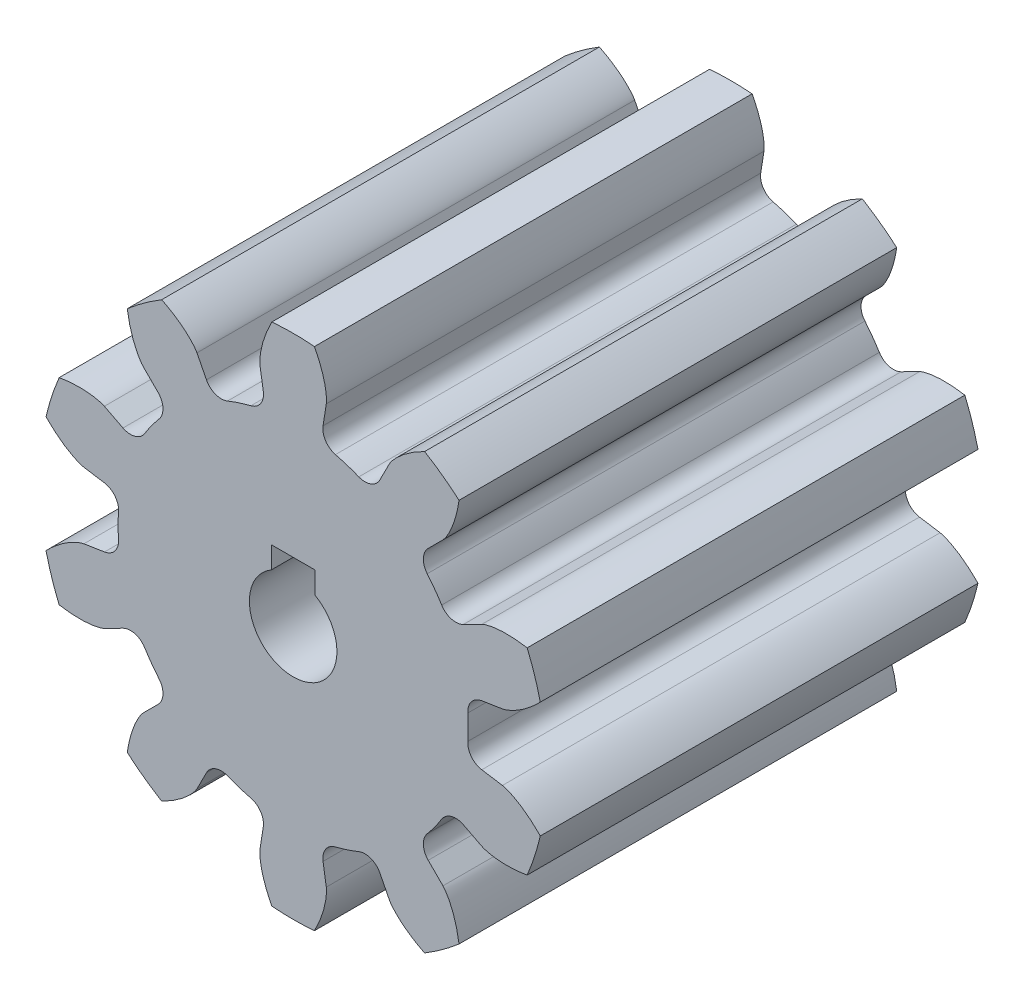
SolidWorks part; units mm, degrees
material "Plain Carbon Steel"
ref_plane "Front Plane" through (0, 0, 0) normal (0, 0, 1) x (1, 0, 0)
ref_plane "Top Plane" through (0, 0, 0) normal (0, 1, 0) x (1, 0, 0)
ref_plane "Right Plane" through (0, 0, 0) normal (1, 0, 0) x (0, 0, -1)
other "Configuration Table"
sketch "Base Circle Sketch" plane through (0, 0, 0) normal (0, 0, 1) x (1, 0, 0)
  circle A0 centre (0, 0) radius 9.6815 construction
  dimension "Base Circle" = 19.363
sketch "Pitch Circle Sketch" plane through (0, 0, 0) normal (0, 0, 1) x (1, 0, 0)
  circle A0 centre (0, 0) radius 10 construction
  dimension "Pitch Circle" = 20
sketch "Outer Dia Sketch" plane through (0, 0, 0) normal (0, 0, 1) x (1, 0, 0)
  circle A0 centre (0, 0) radius 11.6 construction
  dimension "Outer Diameter" = 23.2
sketch "Root Dia Sketch" plane through (0, 0, 0) normal (0, 0, 1) x (1, 0, 0)
  circle A0 centre (0, 0) radius 8
  dimension "Root Circle" = 16
sketch "Involute Sketch" plane through (0, 0, 0) normal (0, 0, 1) x (1, 0, 0)
  line L0 (0, 0) -> (1.5145, 9.5623) construction
  line L2 (0, 0) -> (-1.5145, 9.5623) construction
  line L4 (0, 0) -> (0, 9.6815) construction
  circle A0 centre (0, 0) radius 9.6815 construction
  spline S0 degree 4 poles (1.5145, 9.5623) (1.5152, 9.5666) (1.5169, 9.5789) (1.5193, 9.6022) (1.5218, 9.6404) (1.5232, 9.6893) (1.5229, 9.7525) (1.5198, 9.8272) (1.5134, 9.9092) (1.5034, 9.9985) (1.4907, 10.0875) (1.4754, 10.1761) (1.4579, 10.2642) (1.434, 10.3707) (1.4015, 10.498) (1.3581, 10.6462) (1.3025, 10.8132) (1.239, 10.9822) (1.171, 11.1474) (1.0959, 11.3129) (1.0188, 11.4719) (0.9324, 11.6353) (0.8493, 11.7852) (0.7493, 11.9511) (0.6665, 12.0843) (0.5501, 12.2574) (0.4791, 12.3589) (0.3937, 12.4767) (0.3544, 12.5286) (0.3302, 12.5605) knots 0 0 0 0 0 0.005377 0.015084 0.028532 0.04661 0.064855 0.092111 0.119476 0.146842 0.174209 0.201575 0.228941 0.256307 0.307035 0.361767 0.4165 0.471232 0.525964 0.580697 0.635429 0.690161 0.744894 0.799626 0.854358 0.909091 0.954545 1 1 1 1 1 construction
  spline S1 degree 4 poles (1.5145, 9.5623) (1.5152, 9.5666) (1.5169, 9.5789) (1.5193, 9.6022) (1.5218, 9.6404) (1.5232, 9.6893) (1.5229, 9.7525) (1.5198, 9.8272) (1.5134, 9.9092) (1.5034, 9.9985) (1.4907, 10.0875) (1.4754, 10.1761) (1.4579, 10.2642) (1.434, 10.3707) (1.4015, 10.498) (1.3581, 10.6462) (1.3025, 10.8132) (1.239, 10.9822) (1.171, 11.1474) (1.0959, 11.3129) (1.0188, 11.4719) (0.9324, 11.6353) (0.8493, 11.7852) (0.7493, 11.9511) (0.6665, 12.0843) (0.5753, 12.2199) (0.5301, 12.2856) (0.5067, 12.319) knots 0 0 0 0 0 0.005377 0.015084 0.028532 0.04661 0.064855 0.092111 0.119476 0.146842 0.174209 0.201575 0.228941 0.256307 0.307035 0.361767 0.4165 0.471232 0.525964 0.580697 0.635429 0.690161 0.744894 0.799626 0.854358 0.909091 0.909091 0.909091 0.909091 0.909091
  spline S2 degree 4 poles (-1.5145, 9.5623) (-1.5152, 9.5666) (-1.5169, 9.5789) (-1.5193, 9.6022) (-1.5218, 9.6404) (-1.5232, 9.6893) (-1.5229, 9.7525) (-1.5198, 9.8272) (-1.5134, 9.9092) (-1.5034, 9.9985) (-1.4907, 10.0875) (-1.4754, 10.1761) (-1.4579, 10.2642) (-1.434, 10.3707) (-1.4015, 10.498) (-1.3581, 10.6462) (-1.3025, 10.8132) (-1.239, 10.9822) (-1.171, 11.1474) (-1.0959, 11.3129) (-1.0188, 11.4719) (-0.9324, 11.6353) (-0.8493, 11.7852) (-0.7493, 11.9511) (-0.6665, 12.0843) (-0.5501, 12.2574) (-0.4791, 12.3589) (-0.3937, 12.4767) (-0.3544, 12.5286) (-0.3302, 12.5605) knots 0 0 0 0 0 0.005377 0.015084 0.028532 0.04661 0.064855 0.092111 0.119476 0.146842 0.174209 0.201575 0.228941 0.256307 0.307035 0.361767 0.4165 0.471232 0.525964 0.580697 0.635429 0.690161 0.744894 0.799626 0.854358 0.909091 0.954545 1 1 1 1 1 construction
  spline S3 degree 4 poles (-1.5145, 9.5623) (-1.5152, 9.5666) (-1.5169, 9.5789) (-1.5193, 9.6022) (-1.5218, 9.6404) (-1.5232, 9.6893) (-1.5229, 9.7525) (-1.5198, 9.8272) (-1.5134, 9.9092) (-1.5034, 9.9985) (-1.4907, 10.0875) (-1.4754, 10.1761) (-1.4579, 10.2642) (-1.434, 10.3707) (-1.4015, 10.498) (-1.3581, 10.6462) (-1.3025, 10.8132) (-1.239, 10.9822) (-1.171, 11.1474) (-1.0959, 11.3129) (-1.0188, 11.4719) (-0.9324, 11.6353) (-0.8493, 11.7852) (-0.7493, 11.9511) (-0.6665, 12.0843) (-0.5753, 12.2199) (-0.5301, 12.2856) (-0.5067, 12.319) knots 0 0 0 0 0 0.005377 0.015084 0.028532 0.04661 0.064855 0.092111 0.119476 0.146842 0.174209 0.201575 0.228941 0.256307 0.307035 0.361767 0.4165 0.471232 0.525964 0.580697 0.635429 0.690161 0.744894 0.799626 0.854358 0.909091 0.909091 0.909091 0.909091 0.909091
  dimension "D1" = 18
  dimension "D2" = 9
sketch "Tooth Profile Sketch" plane through (0, 0, 0) normal (0, 0, 1) x (1, 0, 0)
  line L1 (0, 0) -> (-1.5145, 9.5623) construction
  line L2 (1.2515, 7.9015) -> (1.5145, 9.5623)
  line L3 (-1.2515, 7.9015) -> (-1.5145, 9.5623)
  line L4 (0, 0) -> (1.5145, 9.5623) construction
  circle A0 centre (0, 0) radius 11.6 construction
  circle A1 centre (0, 0) radius 8 construction
  arc A2 (0.9722, 11.5592) -> (-0.9722, 11.5592) centre (0, 0) ccw
  arc A3 (1.2515, 7.9015) -> (-1.2515, 7.9015) centre (0, 0) ccw
  spline S0 degree 4 poles (985.6007, 169.3197) (11.931, 10.5269) (-1.1518, 8.7206) (-1.4896, 9.1615) (-1.5218, 9.6404) (-1.5232, 9.6893) (-1.5229, 9.7525) (-1.5198, 9.8272) (-1.5134, 9.9092) (-1.5034, 9.9985) (-1.4907, 10.0875) (-1.4754, 10.1761) (-1.4579, 10.2642) (-1.434, 10.3707) (-1.4015, 10.498) (-1.3581, 10.6462) (-1.3025, 10.8132) (-1.239, 10.9822) (-1.171, 11.1474) (-1.0959, 11.3129) (-1.0188, 11.4719) (-0.9324, 11.6353) (-0.8493, 11.7852) (-0.7493, 11.9511) (-0.3427, 12.6055) (1.1696, 14.6077) (-16.0073, -10.1718) (574.1108, 830.6903) knots -0.537874 -0.537874 -0.537874 -0.537874 -0.537874 0.005377 0.015084 0.028532 0.04661 0.064855 0.092111 0.119476 0.146842 0.174209 0.201575 0.228941 0.256307 0.307035 0.361767 0.4165 0.471232 0.525964 0.580697 0.635429 0.690161 0.744894 0.799626 0.854358 1.76591 1.76591 1.76591 1.76591 1.76591 only from (-1.5145, 9.5623) to (-0.5067, 12.319) construction
  spline S1 degree 4 poles (-985.6007, 169.3197) (-11.931, 10.5269) (1.1518, 8.7206) (1.4896, 9.1615) (1.5218, 9.6404) (1.5232, 9.6893) (1.5229, 9.7525) (1.5198, 9.8272) (1.5134, 9.9092) (1.5034, 9.9985) (1.4907, 10.0875) (1.4754, 10.1761) (1.4579, 10.2642) (1.434, 10.3707) (1.4015, 10.498) (1.3581, 10.6462) (1.3025, 10.8132) (1.239, 10.9822) (1.171, 11.1474) (1.0959, 11.3129) (1.0188, 11.4719) (0.9324, 11.6353) (0.8493, 11.7852) (0.7493, 11.9511) (0.3427, 12.6055) (-1.1696, 14.6077) (16.0073, -10.1718) (-574.1108, 830.6903) knots -0.537874 -0.537874 -0.537874 -0.537874 -0.537874 0.005377 0.015084 0.028532 0.04661 0.064855 0.092111 0.119476 0.146842 0.174209 0.201575 0.228941 0.256307 0.307035 0.361767 0.4165 0.471232 0.525964 0.580697 0.635429 0.690161 0.744894 0.799626 0.854358 1.76591 1.76591 1.76591 1.76591 1.76591 only from (1.5145, 9.5623) to (0.5067, 12.319) construction
  spline S2 degree 4 poles (-1.5145, 9.5623) (-1.5152, 9.5666) (-1.5169, 9.5789) (-1.5193, 9.6022) (-1.5218, 9.6404) (-1.5232, 9.6893) (-1.5229, 9.7525) (-1.5198, 9.8272) (-1.5134, 9.9092) (-1.5034, 9.9985) (-1.4907, 10.0875) (-1.4754, 10.1761) (-1.4579, 10.2642) (-1.434, 10.3707) (-1.4015, 10.498) (-1.3581, 10.6462) (-1.3025, 10.8132) (-1.239, 10.9822) (-1.171, 11.1474) (-1.0959, 11.3129) (-1.0374, 11.4336) (-0.9949, 11.5161) (-0.973, 11.5577) (-0.9722, 11.5592) knots 0 0 0 0 0 0.005377 0.015084 0.028532 0.04661 0.064855 0.092111 0.119476 0.146842 0.174209 0.201575 0.228941 0.256307 0.307035 0.361767 0.4165 0.471232 0.525964 0.580697 0.635429 0.637473 0.637473 0.637473 0.637473 0.637473
  spline S3 degree 4 poles (1.5145, 9.5623) (1.5152, 9.5666) (1.5169, 9.5789) (1.5193, 9.6022) (1.5218, 9.6404) (1.5232, 9.6893) (1.5229, 9.7525) (1.5198, 9.8272) (1.5134, 9.9092) (1.5034, 9.9985) (1.4907, 10.0875) (1.4754, 10.1761) (1.4579, 10.2642) (1.434, 10.3707) (1.4015, 10.498) (1.3581, 10.6462) (1.3025, 10.8132) (1.239, 10.9822) (1.171, 11.1474) (1.0959, 11.3129) (1.0374, 11.4336) (0.9949, 11.5161) (0.973, 11.5577) (0.9722, 11.5592) knots 0 0 0 0 0 0.005377 0.015084 0.028532 0.04661 0.064855 0.092111 0.119476 0.146842 0.174209 0.201575 0.228941 0.256307 0.307035 0.361767 0.4165 0.471232 0.525964 0.580697 0.635429 0.637473 0.637473 0.637473 0.637473 0.637473
extrude "Root Circle Extrude" add sketch "Root Dia Sketch" along normal mid plane 20
extrude "Tooth Profile Extrude" add sketch "Tooth Profile Sketch" along normal up to surface and the other way up to surface up to face at (8, 0, 10) other way up to face at (8, 0, -10)
fillet "Root Radius Fillet" radius 0.76 2 edges at (-1.2515, 7.9015, 0) (1.2515, 7.9015, 0)
pattern_circular "CirPattern1" count 10 over 360 about axis through (0, 0, 10) along (0, 0, -1) of "Tooth Profile Extrude", "Root Radius Fillet"
sketch "Sketch1" plane through (0, 0, 10) normal (0, 0, 1) x (1, 0, 0)
  circle A0 centre (0, 0) radius 2
  dimension "D1" = 4
extrude "Cut-Extrude1" cut sketch "Sketch1" against normal through all both and the other way through all
sketch "Sketch2" plane through (0, 0, 10) normal (0, 0, 1) x (1, 0, 0)
  line L1 (-1, 1.7321) -> (1, 1.7321)
  line L2 (-1, 1.7321) -> (-1, 2.7321)
  line L3 (-1, 2.7321) -> (1, 2.7321)
  line L4 (1, 1.7321) -> (1, 2.7321)
  circle A0 centre (0, 0) radius 2 construction
  dimension "D2" = 1
  dimension "D1" = 2
extrude "Cut-Extrude2" cut sketch "Sketch2" against normal through all and the other way through all contours L3 L4 L1 L2
equation "\"Module\"= 2"
equation "\"Number of Teeth\" = 10"
equation "\"Pressure Angle\"= 14.5"
equation "\"Pitch Circle Diameter\"= \"Module\" * \"Number of Teeth\""
equation "\"Addendum\"= IIF ( \"Stub Teeth\" = 0 , \"Module\" , 0.8 * \"Module\" )"
equation "\"Dedendum\"= IIF ( \"Stub Teeth\" = 0 , 1.25 * \"Module\" , \"Module\" )"
equation "\"Outer Diameter\"= \"Pitch Circle Diameter\" + \"Addendum\" * 2"
equation "\"Root Circle Diameter\"= \"Pitch Circle Diameter\" - \"Dedendum\" * 2"
equation "\"Base Circle Diameter\"= \"Pitch Circle Diameter\" * cos ( \"Pressure Angle\" )"
equation "\"Root Fillet\"= \"Module\" * 0.38"
equation "\"Base Circle@Base Circle Sketch\" = \"Base Circle Diameter\""
equation "\"Pitch Circle@Pitch Circle Sketch\" = \"Pitch Circle Diameter\""
equation "\"Outer Diameter@Outer Dia Sketch\" = \"Outer Diameter\""
equation "\"Circular Pitch\"= pi * \"Module\""
equation "\"Pitch Angle\"= 360 / \"Number of Teeth\""
equation "\"Arc Length\"= \"Pitch Angle\" * ( \"Base Circle Diameter\" / 2 ) * ( pi / 180 )"
equation "\"Stub Teeth\" = 1'Zero for No - One for Yes"
equation "\"Root Circle@Root Dia Sketch\"=\"Root Circle Diameter\""
equation "\"D1@Involute Sketch\"=\"Pitch Angle\" / 2"
equation "\"D2@Involute Sketch\"=\"Pitch Angle\" / 4"
equation "\"D1@Root Radius Fillet\"=\"Root Fillet\""
equation "\"D1@CirPattern1\"=\"Number of Teeth\""
equation "\"D1@Sketch1\"=\"Pitch Circle Diameter\" / 5"
equation "\"D2@Sketch2\"= \"D1@Sketch1\" / 4"
equation "\"D1@Sketch2\"= \"D1@Sketch1\" / 2"
